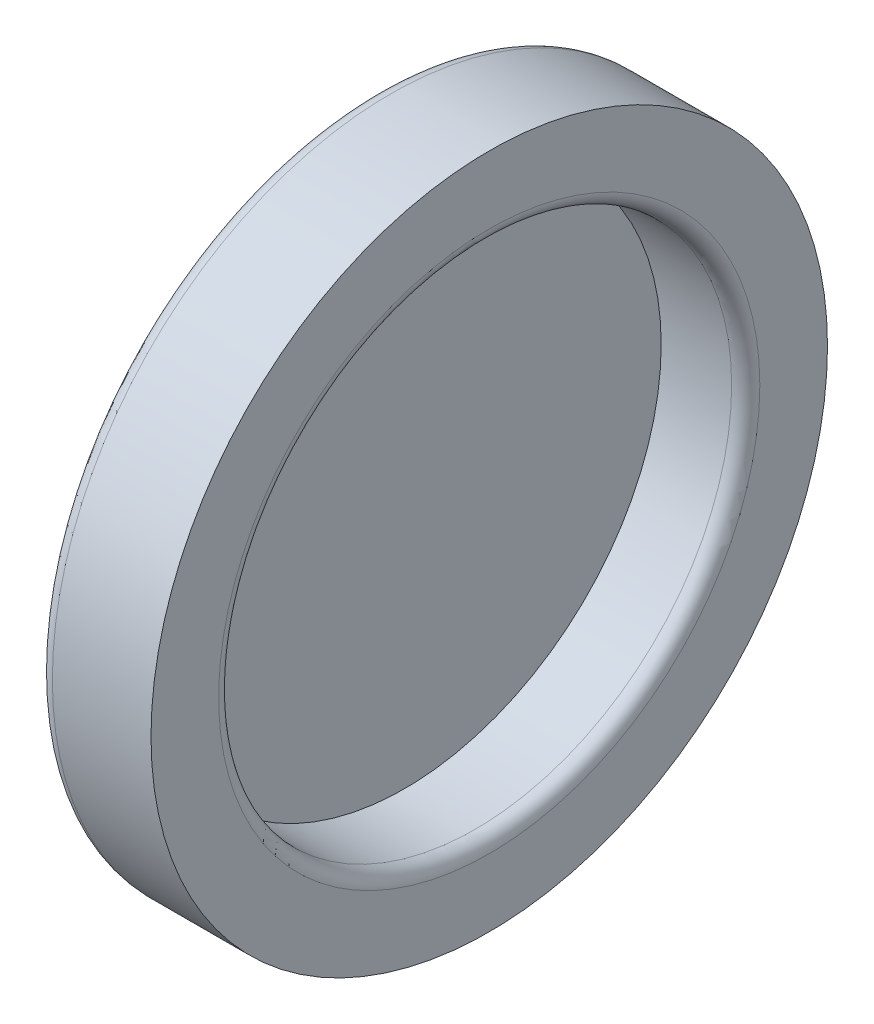
SolidWorks part; units mm, degrees
ref_plane "前视基准面" through (0, 0, 0) normal (0, 0, 1) x (1, 0, 0)
ref_plane "上视基准面" through (0, 0, 0) normal (0, 1, 0) x (1, 0, 0)
ref_plane "右视基准面" through (0, 0, 0) normal (1, 0, 0) x (0, 0, -1)
other "Configuration Table"
sketch "草图1" plane through (0, 0, 0) normal (1, 0, 0) x (0, 0, -1)
  circle A1 centre (0, 0) radius 12
  dimension "D2" = 24
extrude "凸台-拉伸1" add sketch "草图1" along normal blind 4
sketch "草图2" plane through (4, 0, 0) normal (1, 0, 0) x (0, 0, -1)
  circle A0 centre (0, 0) radius 9.1
  dimension "D1" = 18.2
extrude "切除-拉伸1" cut sketch "草图2" against normal blind 3
fillet "圆角1" radius 0.5 1 edges at (4, 0, -9.1)
fillet "圆角2" radius 0.5 1 edges at (0, 0, -12)
